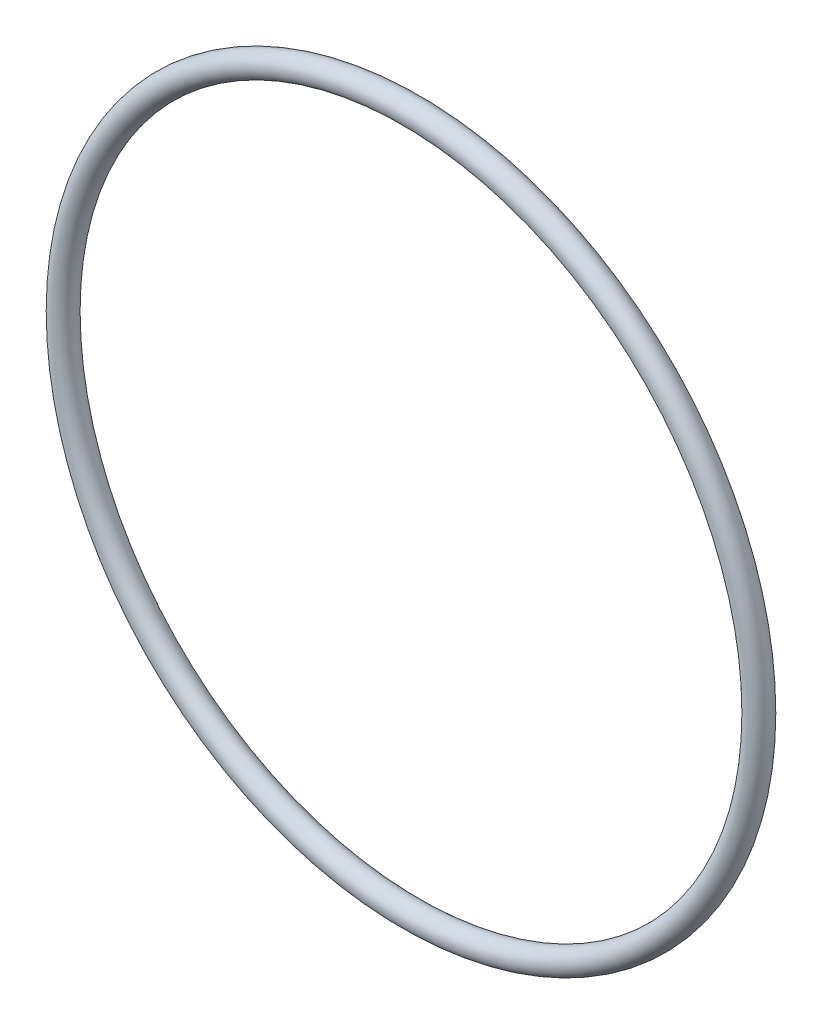
SolidWorks part; units mm, degrees
ref_plane "Plan de face" through (0, 0, 0) normal (0, 0, 1) x (1, 0, 0)
ref_plane "Plan de dessus" through (0, 0, 0) normal (0, 1, 0) x (1, 0, 0)
ref_plane "Plan de droite" through (0, 0, 0) normal (1, 0, 0) x (0, 0, -1)
ref_axis "Axe1" through (0, 0, -88.99) along (0, 0, 1)
sketch "Esquisse1" plane through (0, 0, 0) normal (1, 0, 0) x (0, 0, -1)
  line L0 (0, 29) -> (0, 0) construction
  circle A0 centre (0, 29) radius 1
  dimension "D1" = 2
  dimension "D2" = 29
revolve "Révolution1" add sketch "Esquisse1" angle 360 about axis through (0, 0, -88.99) along (0, 0, 1)
